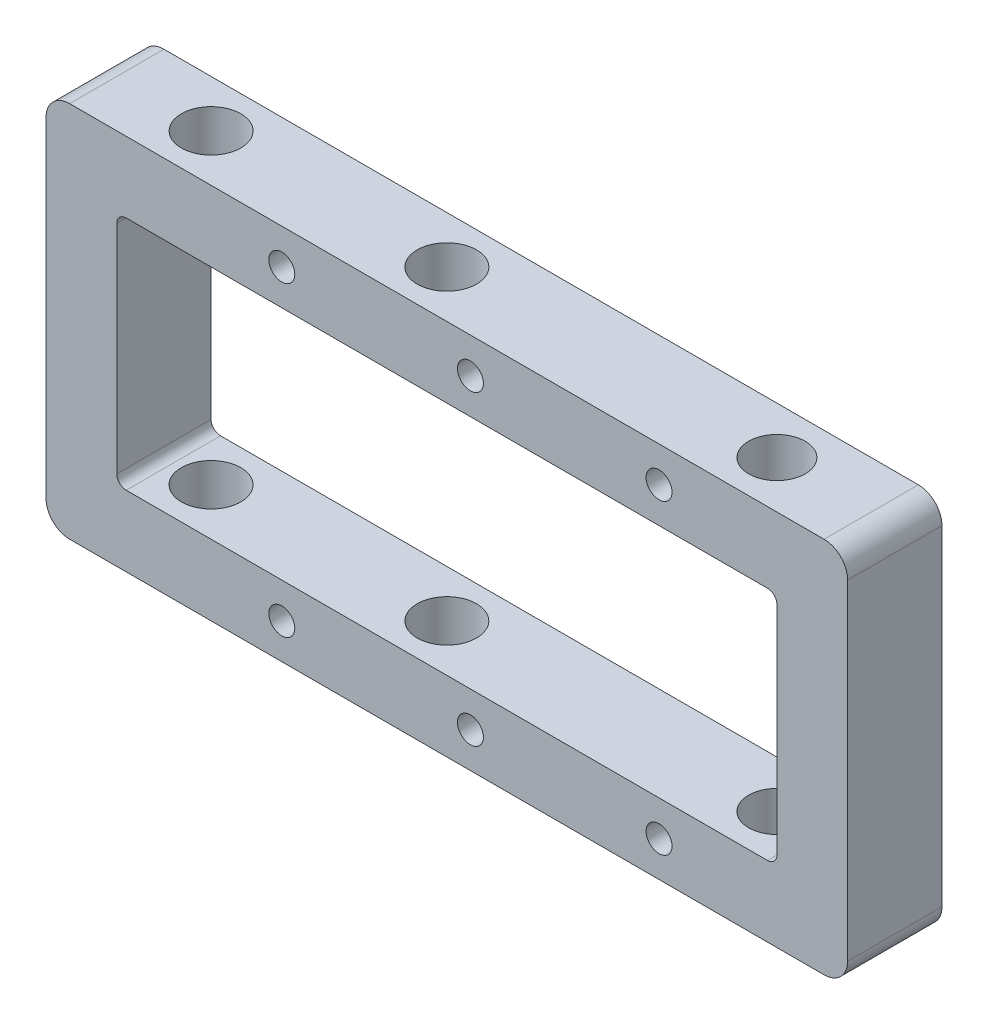
SolidWorks part; units mm, degrees
ref_plane "Front Plane" through (0, 0, 0) normal (0, 0, 1) x (1, 0, 0)
ref_plane "Top Plane" through (0, 0, 0) normal (0, 1, 0) x (1, 0, 0)
ref_plane "Right Plane" through (0, 0, 0) normal (1, 0, 0) x (0, 0, -1)
sketch "Sketch1" plane through (0, 0, 0) normal (0, 0, 1) x (1, 0, 0)
  line L1 (-85, 40) -> (85, 40)
  line L2 (-85, 40) -> (-85, -40)
  line L3 (-85, -40) -> (85, -40)
  line L4 (85, 40) -> (85, -40)
  line L5 (-85, 40) -> (85, -40) construction
  line L6 (-85, -40) -> (85, 40) construction
  line L7 (-70, 25) -> (70, 25)
  line L8 (-70, 25) -> (-70, -25)
  line L9 (-70, -25) -> (70, -25)
  line L10 (70, 25) -> (70, -25)
  line L11 (-70, 25) -> (70, -25) construction
  line L12 (-70, -25) -> (70, 25) construction
  point P0 (0, 0)
  point P6 (0, 0)
  dimension "D1" = 140
  dimension "D2" = 15
  dimension "D3" = 50
  dimension "D4" = 80
extrude "Boss-Extrude1" add sketch "Sketch1" along normal blind 20
sketch "Sketch2" plane through (0, 40, 0) normal (0, 1, 0) x (1, 0, 0)
  line L0 (85, -20) -> (-85, -20) construction
  line L1 (-85, -20) -> (-85, 0) construction
  circle A0 centre (-60, -10) radius 6.3
  circle A1 centre (-10, -10) radius 6.3
  dimension "D3" = 12.6
  dimension "D1" = 50
  dimension "D2" = 25
  dimension "D4" = 10
extrude "Cut-Extrude1" cut sketch "Sketch2" against normal through all and the other way through all
sketch "Sketch5" plane through (0, 0, 0) normal (0, 0, -1) x (-1, 0, 0)
  line L0 (-70, 25) -> (70, 25) construction
  line L1 (70, -25) -> (-70, -25) construction
  line L3 (85, 40) -> (85, -40) construction
  circle A0 centre (35, 32.5) radius 2.75
  circle A1 centre (35, -32.5) radius 2.75
  circle A2 centre (-5, 32.5) radius 2.75
  circle A3 centre (-5, -32.5) radius 2.75
  dimension "D1" = 5.5
  dimension "D2" = 7.5
  dimension "D3" = 7.5
  dimension "D4" = 40
  dimension "D5" = 50
extrude "Cut-Extrude3" cut sketch "Sketch5" against normal up to next
fillet "Fillet1" radius 2 4 edges at (-70, 25, 10) (-70, -25, 10) (70, -25, 10) (70, 25, 10)
fillet "Fillet2" radius 5 4 edges at (-85, 40, 10) (-85, -40, 10) (85, -40, 10) (85, 40, 10)
sketch "Sketch6" plane through (0, 40, 0) normal (0, 1, 0) x (1, 0, 0)
  line L0 (85, 0) -> (85, -20) construction
  circle A0 centre (60, -10) radius 6
  point P2 (0, 0)
  dimension "D2" = 12
  dimension "D1" = 25
extrude "Cut-Extrude4" cut sketch "Sketch6" against normal through all contours A0
sketch "Sketch7" plane through (0, 0, 0) normal (0, 0, -1) x (-1, 0, 0)
  circle A0 centre (-45, 32.5) radius 2.75
  circle A1 centre (-45, -32.5) radius 2.75
  point P4 (0, 0)
  point P7 (0, 0)
  dimension "D2" = 5.5
  dimension "D1" = 40
extrude "Cut-Extrude5" cut sketch "Sketch7" against normal through all
